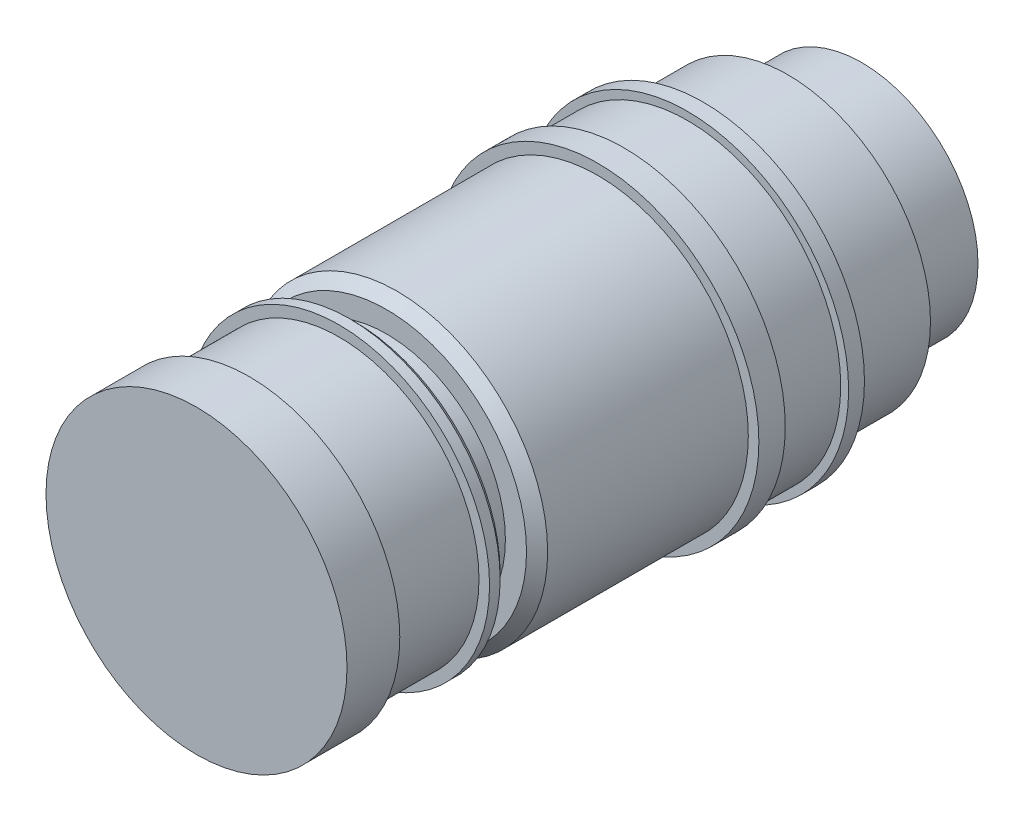
SolidWorks part; units mm, degrees
ref_plane "Front Plane" through (0, 0, 0) normal (0, 0, 1) x (1, 0, 0)
ref_plane "Top Plane" through (0, 0, 0) normal (0, 1, 0) x (1, 0, 0)
ref_plane "Right Plane" through (0, 0, 0) normal (1, 0, 0) x (0, 0, -1)
sketch "Sketch1" plane through (0, 0, 0) normal (1, 0, 0) x (0, 0, -1)
  line L1 (0, 0) -> (5, 0)
  line L2 (0, 0) -> (0, 14.25)
  line L3 (0, 14.25) -> (5, 14.25)
  line L4 (5, 0) -> (5, 14.25)
  line L5 (5, 0) -> (13.5, 0)
  line L6 (5, 0) -> (5, 13.25)
  line L7 (5, 13.25) -> (13.5, 13.25)
  line L8 (13.5, 0) -> (13.5, 13.25)
  line L10 (13.5, 0) -> (13.5, 11.25)
  line L41 (13.5, 0) -> (15, 0)
  line L42 (13.5, 0) -> (13.5, 14.25)
  line L43 (13.5, 14.25) -> (15, 14.25)
  line L44 (15, 0) -> (15, 14.25)
  line L45 (15, 0) -> (18, 0)
  line L46 (15, 0) -> (15, 11.25)
  line L47 (15, 11.25) -> (18, 11.25)
  line L48 (18, 0) -> (18, 11.25)
  line L49 (18, 0) -> (38, 0)
  line L50 (18, 0) -> (18, 14.25)
  line L51 (18, 14.25) -> (38, 14.25)
  line L52 (38, 0) -> (38, 14.25)
  line L53 (38, 0) -> (40.5, 0)
  line L54 (38, 0) -> (38, 15.25)
  line L55 (38, 15.25) -> (40.5, 15.25)
  line L56 (40.5, 0) -> (40.5, 15.25)
  line L57 (40.5, 0) -> (46.5, 0)
  line L58 (40.5, 0) -> (40.5, 14.5)
  line L59 (40.5, 14.5) -> (46.5, 14.5)
  line L60 (46.5, 0) -> (46.5, 14.5)
  line L61 (46.5, 0) -> (48, 0)
  line L62 (46.5, 0) -> (46.5, 15.25)
  line L63 (46.5, 15.25) -> (48, 15.25)
  line L64 (48, 0) -> (48, 15.25)
  line L65 (48, 0) -> (56, 0)
  line L66 (48, 0) -> (48, 13.5)
  line L67 (48, 13.5) -> (56, 13.5)
  line L68 (56, 0) -> (56, 13.5)
  line L69 (56, 0) -> (63, 0)
  line L70 (56, 0) -> (56, 11)
  line L71 (56, 11) -> (63, 11)
  line L72 (63, 0) -> (63, 11)
  dimension "D1" = 14.25
  dimension "D2" = 13.25
  dimension "D3" = 14.25
  dimension "D4" = 5
  dimension "D5" = 8.5
  dimension "D6" = 1.5
  dimension "D7" = 11.25
  dimension "D8" = 3
  dimension "D9" = 14.25
  dimension "D10" = 20
  dimension "D11" = 15.25
  dimension "D12" = 2.5
  dimension "D13" = 6
  dimension "D14" = 14.5
  dimension "D15" = 1.5
  dimension "D16" = 15.25
  dimension "D17" = 8
  dimension "D18" = 13.5
  dimension "D19" = 7
  dimension "D20" = 11
revolve "Revolve1" add sketch "Sketch1" angle 360 about L5
chamfer "Chamfer1" distance 1 angle 45 1 edges at (14.25, 0, -18)
chamfer "Chamfer2" distance 0.5 angle 45 1 edges at (14.25, 0, -15)
